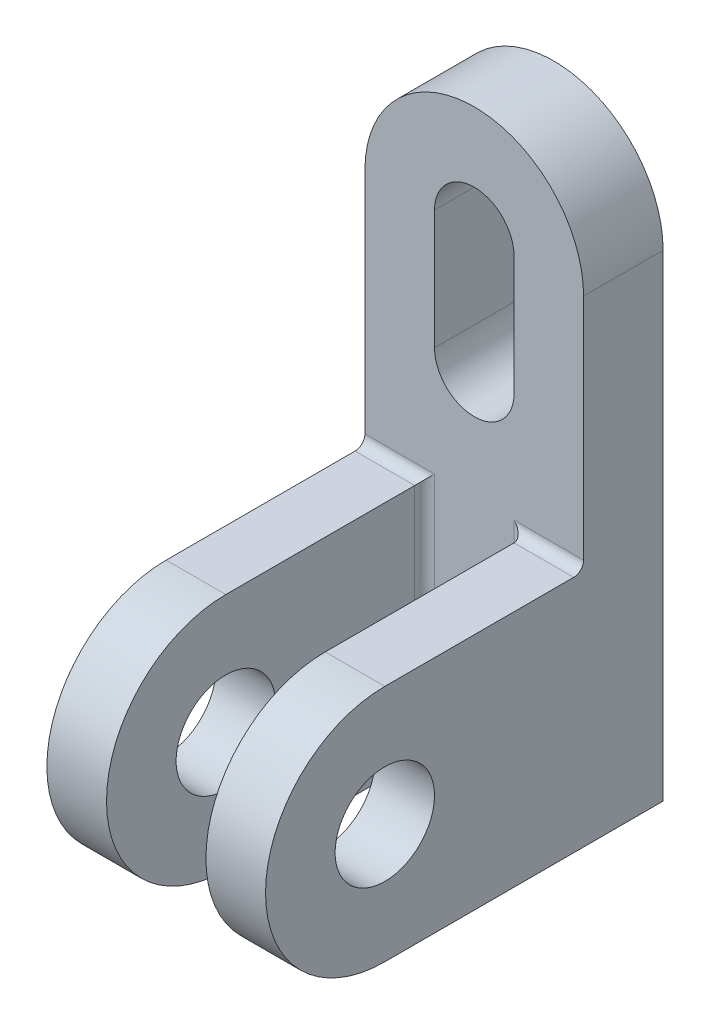
SolidWorks part; units mm, degrees
ref_plane "Plan de face" through (0, 0, 0) normal (1, 0, 0) x (0, 1, 0)
ref_plane "Plan de dessus" through (0, 0, 0) normal (0, 0, 1) x (0, 1, 0)
ref_plane "Plan de droite" through (0, 0, 0) normal (0, 1, 0) x (-1, 0, 0)
sketch "Esquisse1" plane through (0, 0, 0) normal (0, 0, 1) x (0, 1, 0)
  line L1 (-59, -22) -> (59, -22)
  line L2 (-59, -22) -> (-59, 22)
  line L3 (-59, 22) -> (59, 22)
  line L4 (59, -22) -> (59, 22)
  line L5 (-59, -22) -> (59, 22) construction
  line L6 (-59, 22) -> (59, -22) construction
  circle A1 centre (37, 0) radius 22
  point P0 (0, 0)
  dimension "D1" = 118
  dimension "D2" = 44
extrude "Boss.-Extru.1" add sketch "Esquisse1" along normal blind 16 contours A1 L3 L2 L1 | A1
sketch "Esquisse2" plane through (0, 0, 0) normal (0, 0, -1) x (1, 0, 0)
  line L0 (0, -37) -> (0, -13) construction
  line L1 (-8, -37) -> (-8, -13)
  line L2 (8, -37) -> (8, -13)
  arc A0 (-8, -37) -> (8, -37) centre (0, -37) ccw
  arc A1 (8, -13) -> (-8, -13) centre (0, -13) ccw
  point P4 (0, -25)
  dimension "D1" = 8
  dimension "D2" = 24
extrude "Enlèv. mat.-Extru.1" cut sketch "Esquisse2" against normal blind 16
sketch "Esquisse3" plane through (22, 0, 0) normal (1, 0, 0) x (0, 1, 0)
  line L5 (-59, 16) -> (-11, 16)
  line L6 (-59, 16) -> (-59, 56)
  line L7 (-59, 56) -> (-11, 56)
  line L8 (-11, 16) -> (-11, 56)
  circle A1 centre (-35, 56) radius 24
  circle A2 centre (-35, 56) radius 10
  line M6 (37, 16) -> (-59, 16)
  dimension "D3" = 20
  dimension "D1" = 40
  dimension "D2" = 48
extrude "Boss.-Extru.3" add sketch "Esquisse3" against normal blind 12 contours A1 L6 L8 M6 | A2 L7 A1 | A2 L7 A1
mirror "Symétrie1" about plane through (0, 0, 0) normal (1, 0, 0) of "Boss.-Extru.3"
fillet "Congé2" radius 2 4 edges at (16, -11, 16) (10, -35, 16) (-16, -11, 16) (-10, -35, 16)
